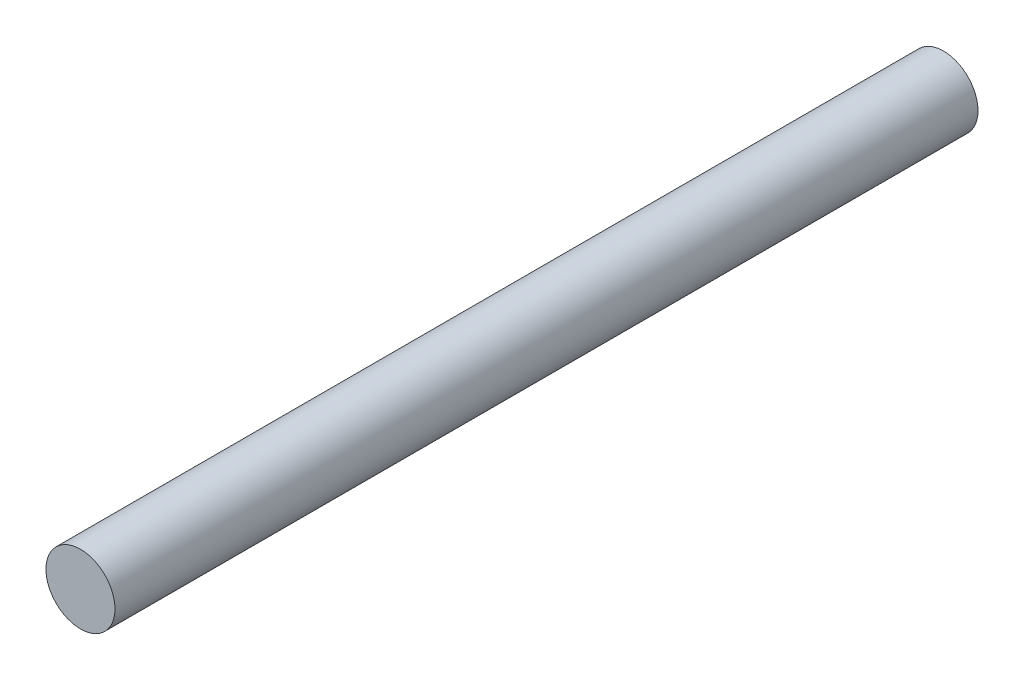
SolidWorks part; units mm, degrees
ref_plane "Front Plane" through (0, 0, 0) normal (0, 0, 1) x (1, 0, 0)
ref_plane "Top Plane" through (0, 0, 0) normal (0, 1, 0) x (1, 0, 0)
ref_plane "Right Plane" through (0, 0, 0) normal (1, 0, 0) x (0, 0, -1)
sketch "Sketch1" plane through (0, 0, 0) normal (0, 0, 1) x (1, 0, 0)
  circle A0 centre (0, 0) radius 4
  dimension "D1" = 8
extrude "Boss-Extrude1" add sketch "Sketch1" along normal mid plane 100
